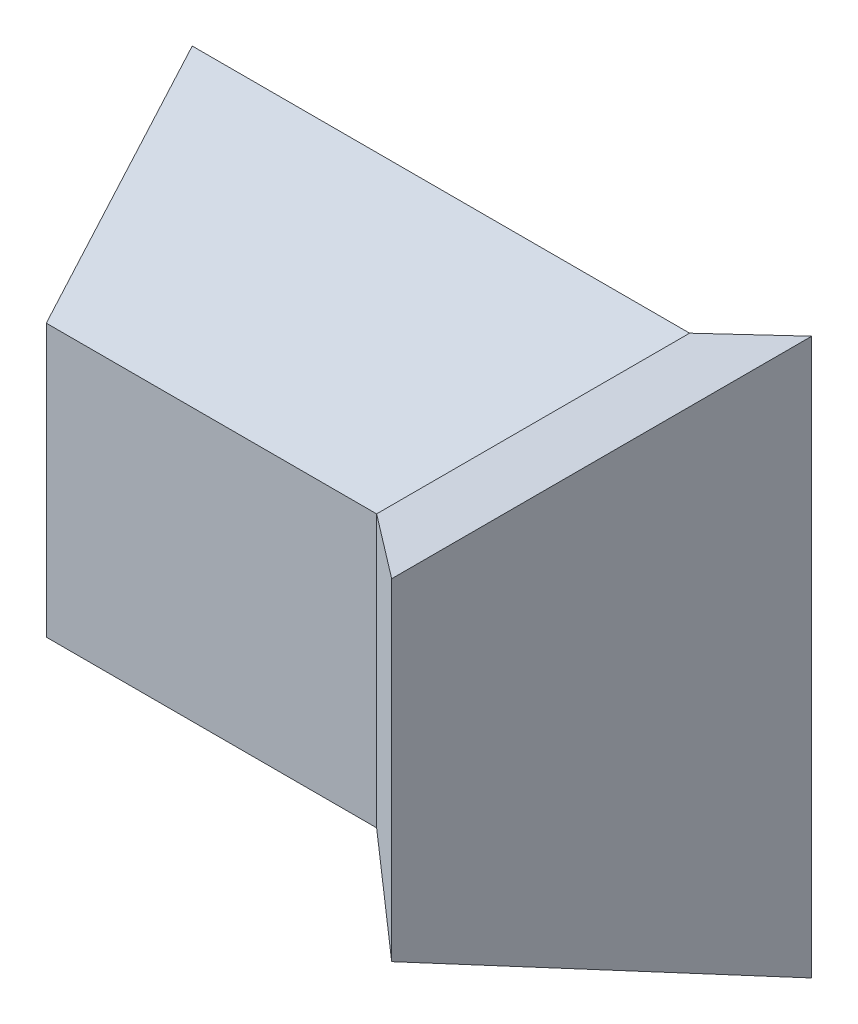
SolidWorks part; units mm, degrees
ref_plane "Спереди" through (0, 0, 0) normal (0, 0, 1) x (1, 0, 0)
ref_plane "Сверху" through (0, 0, 0) normal (0, 1, 0) x (1, 0, 0)
ref_plane "Справа" through (0, 0, 0) normal (1, 0, 0) x (0, 0, -1)
sketch "Эскиз1_fr" plane through (0, 0, 0) normal (0, 0, 1) x (1, 0, 0)
  line L1 (0, 0) -> (43.3507, 0)
  line L2 (0, 0) -> (0, -38.2597)
  line L3 (0, -38.2597) -> (43.3507, -38.2597)
  line L4 (43.3507, 0) -> (43.3507, -38.2597)
extrude "Бобышка-Вытянуть1" add sketch "Эскиз1_fr" along normal blind 20 draft 20
surface "Поверхность-Вытянуть1" parameters "D1"=10, "D3"=20
